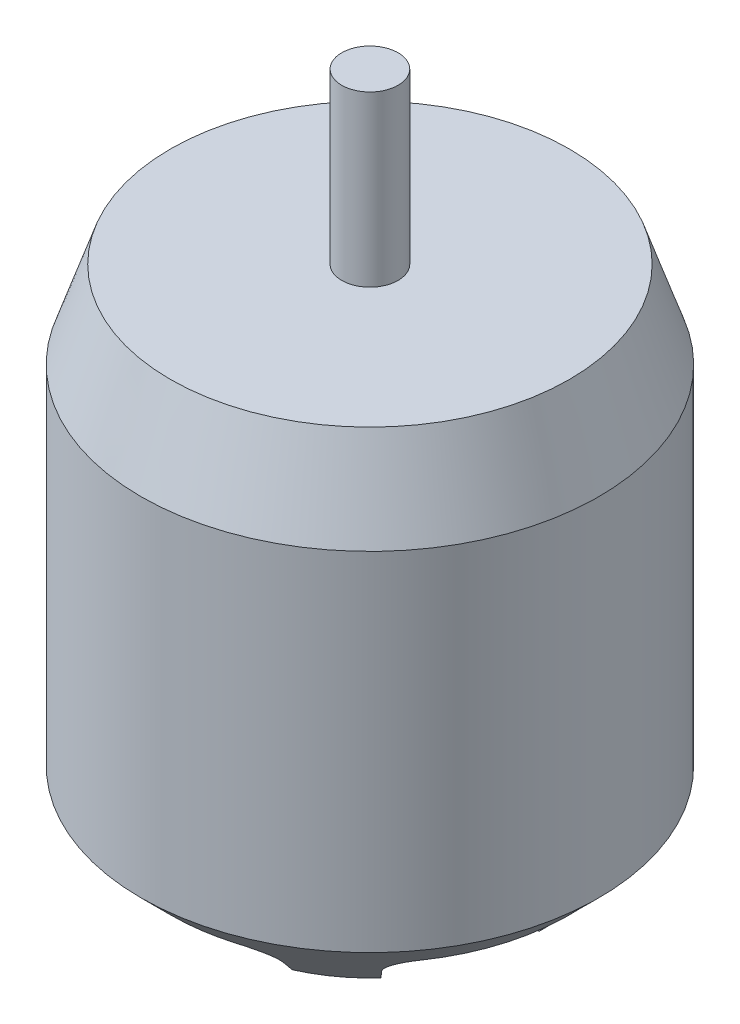
SolidWorks part; units mm, degrees
ref_plane "Front Plane" through (0, 0, 0) normal (0, 0, 1) x (1, 0, 0)
ref_plane "Top Plane" through (0, 0, 0) normal (0, 1, 0) x (1, 0, 0)
ref_plane "Right Plane" through (0, 0, 0) normal (1, 0, 0) x (0, 0, -1)
sketch "Sketch1" plane through (0, 0, 0) normal (0, 1, 0) x (1, 0, 0)
  circle A0 centre (0, 0) radius 24.375
extrude "Boss-Extrude1" add sketch "Sketch1" along normal blind 54.25
chamfer "Chamfer1" distance 9.25 distance2 3.125 1 edges at (0, 54.25, 24.375)
chamfer "Chamfer2" distance 8 angle 45 1 edges at (0, 0, 24.375)
sketch "Sketch2" plane through (0, 0, 0) normal (0, -1, 0) x (1, 0, 0)
  line L0 (-3.7524, -18.0588) -> (-3.1279, -14.701)
  line L1 (-18.3345, -2.0117) -> (-14.9481, -1.568)
  line L2 (3.7524, -18.0588) -> (3.1279, -14.701)
  line L3 (-16.0154, -9.1493) -> (-13.0149, -7.5177)
  line L4 (-7.5789, 16.8155) -> (-6.1105, 13.7319)
  line L5 (-13.6505, 12.4042) -> (-11.1716, 10.0548)
  line L6 (13.6505, 12.4042) -> (11.1716, 10.0548)
  line L7 (7.5789, 16.8155) -> (6.1105, 13.7319)
  line L8 (16.0154, -9.1493) -> (13.0149, -7.5177)
  line L9 (18.3345, -2.0117) -> (14.9481, -1.568)
  arc A0 (7.0421, -19.9592) -> (16.8062, -12.8652) centre (0, 0) ccw
  arc A1 (4.6731, -11.9165) -> (9.8892, -8.1268) centre (0, 0) ccw
  arc A2 (-3.7524, -18.0588) -> (-7.0421, -19.9592) centre (-6.2103, -17.6017) cw
  arc A3 (-4.6731, -11.9165) -> (-3.1279, -14.701) centre (-5.5858, -14.2439) cw
  arc A4 (3.1279, -14.701) -> (4.6731, -11.9165) centre (5.5858, -14.2439) cw
  arc A5 (7.0421, -19.9592) -> (3.7524, -18.0588) centre (6.2103, -17.6017) cw
  arc A6 (-18.3345, -2.0117) -> (-21.1585, 0.5297) centre (-18.6593, 0.4671) cw
  arc A7 (-12.7773, 0.762) -> (-14.9481, -1.568) centre (-15.2729, 0.9108) cw
  arc A8 (-13.0149, -7.5177) -> (-9.8892, -8.1268) centre (-11.8207, -9.714) cw
  arc A9 (-16.8062, -12.8652) -> (-16.0154, -9.1493) centre (-14.8211, -11.3456) cw
  arc A10 (-7.5789, 16.8155) -> (-6.0346, 20.2866) centre (-5.3218, 17.8904) cw
  arc A11 (-3.2237, 12.3874) -> (-6.1105, 13.7319) centre (-3.8534, 14.8068) cw
  arc A12 (-11.1716, 10.0548) -> (-10.7849, 6.8939) centre (-12.8914, 8.2403) cw
  arc A13 (-17.4289, 12.0081) -> (-13.6505, 12.4042) centre (-15.3702, 10.5897) cw
  arc A14 (13.6505, 12.4042) -> (17.4289, 12.0081) centre (15.3702, 10.5897) cw
  arc A15 (10.7849, 6.8939) -> (11.1716, 10.0548) centre (12.8914, 8.2403) cw
  arc A16 (6.1105, 13.7319) -> (3.2237, 12.3874) centre (3.8534, 14.8068) cw
  arc A17 (6.0346, 20.2866) -> (7.5789, 16.8155) centre (5.3218, 17.8904) cw
  arc A18 (16.0154, -9.1493) -> (16.8062, -12.8652) centre (14.8211, -11.3456) cw
  arc A19 (9.8892, -8.1268) -> (13.0149, -7.5177) centre (11.8207, -9.714) cw
  arc A20 (14.9481, -1.568) -> (12.7773, 0.762) centre (15.2729, 0.9108) cw
  arc A21 (21.1585, 0.5297) -> (18.3345, -2.0117) centre (18.6593, 0.4671) cw
  arc A22 (-16.8062, -12.8652) -> (-7.0421, -19.9592) centre (0, 0) ccw
  arc A23 (-9.8892, -8.1268) -> (-4.6731, -11.9165) centre (0, 0) ccw
  arc A24 (12.7773, 0.762) -> (10.7849, 6.8939) centre (0, 0) ccw
  arc A25 (21.1585, 0.5297) -> (17.4289, 12.0081) centre (0, 0) ccw
  arc A26 (-10.7849, 6.8939) -> (-12.7773, 0.762) centre (0, 0) ccw
  arc A27 (-17.4289, 12.0081) -> (-21.1585, 0.5297) centre (0, 0) ccw
  arc A28 (3.2237, 12.3874) -> (-3.2237, 12.3874) centre (0, 0) ccw
  arc A29 (6.0346, 20.2866) -> (-6.0346, 20.2866) centre (0, 0) ccw
  point P4 (-4.25, -20.734)
  point P5 (-2.72, -12.5077)
  point P6 (0, -21.1651)
  point P7 (-4.25, -20.734)
  point P8 (0, -12.8)
  point P15 (-2.72, -12.5077)
  point P71 (0, 0)
  dimension "D1" = 25.6
  dimension "D4" = 42.3302
  dimension "D5" = 2.5
  dimension "D6" = 2.5
  dimension "D2" = 4.25
  dimension "D3" = 2.72
  dimension "D7" = 5
extrude "Cut-Extrude1" cut sketch "Sketch2" against normal blind 10
sketch "Sketch3" plane through (0, 0, 0) normal (0, -1, 0) x (-1, 0, 0)
  circle A0 centre (0, 0) radius 7
extrude "Boss-Extrude2" add sketch "Sketch3" along normal blind 5
sketch "Sketch4" plane through (0, 54.25, 0) normal (0, 1, 0) x (1, 0, 0)
  circle A0 centre (0, 0) radius 3
extrude "Boss-Extrude3" add sketch "Sketch4" along normal blind 18
